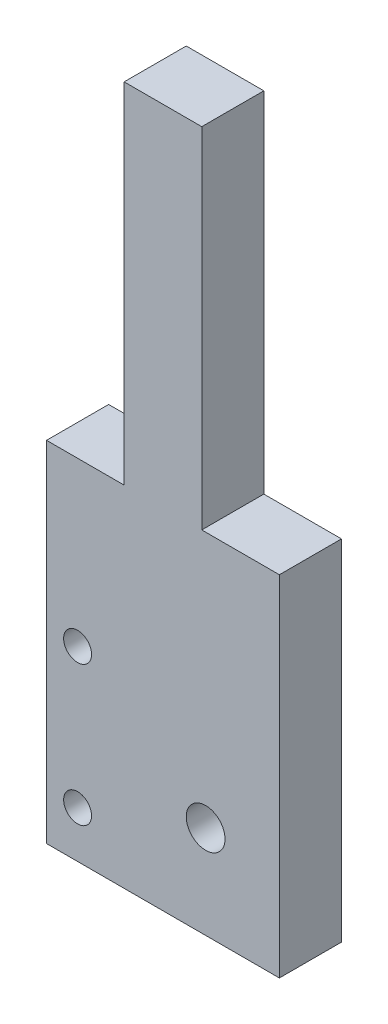
SolidWorks part; units mm, degrees
ref_plane "Front Plane" through (0, 0, 0) normal (0, 0, 1) x (1, 0, 0)
ref_plane "Top Plane" through (0, 0, 0) normal (0, 1, 0) x (1, 0, 0)
ref_plane "Right Plane" through (0, 0, 0) normal (1, 0, 0) x (0, 0, -1)
sketch "Sketch1" plane through (0, 0, 0) normal (0, 0, 1) x (1, 0, 0)
  line L0 (0, 57.15) -> (12.7, 57.15)
  line L1 (0, 0) -> (38.1, 0)
  line L5 (12.7, 57.15) -> (12.7, 114.3)
  line L6 (12.7, 114.3) -> (25.4, 114.3)
  line L7 (25.4, 114.3) -> (25.4, 57.15)
  line L8 (25.4, 57.15) -> (38.1, 57.15)
  line L9 (0, 57.15) -> (0, 0)
  line L10 (38.1, 57.15) -> (38.1, 0)
  circle A0 centre (5.08, 7.62) radius 2.286
  circle A1 centre (5.08, 30.48) radius 2.286
  circle A2 centre (26.035, 15.24) radius 3.175
  point P1 (0, 0)
  point P11 (29.21, 15.24)
  point P12 (22.86, 15.24)
  dimension "D3" = 7.62
  dimension "D5" = 4.572
  dimension "D6" = 4.572
  dimension "D8" = 29.21
  dimension "D9" = 12.7
  dimension "D1" = 38.1
  dimension "D2" = 5.08
  dimension "D4" = 22.86
  dimension "D7" = 22.86
extrude "Boss-Extrude1" add sketch "Sketch1" along normal blind 10.16
